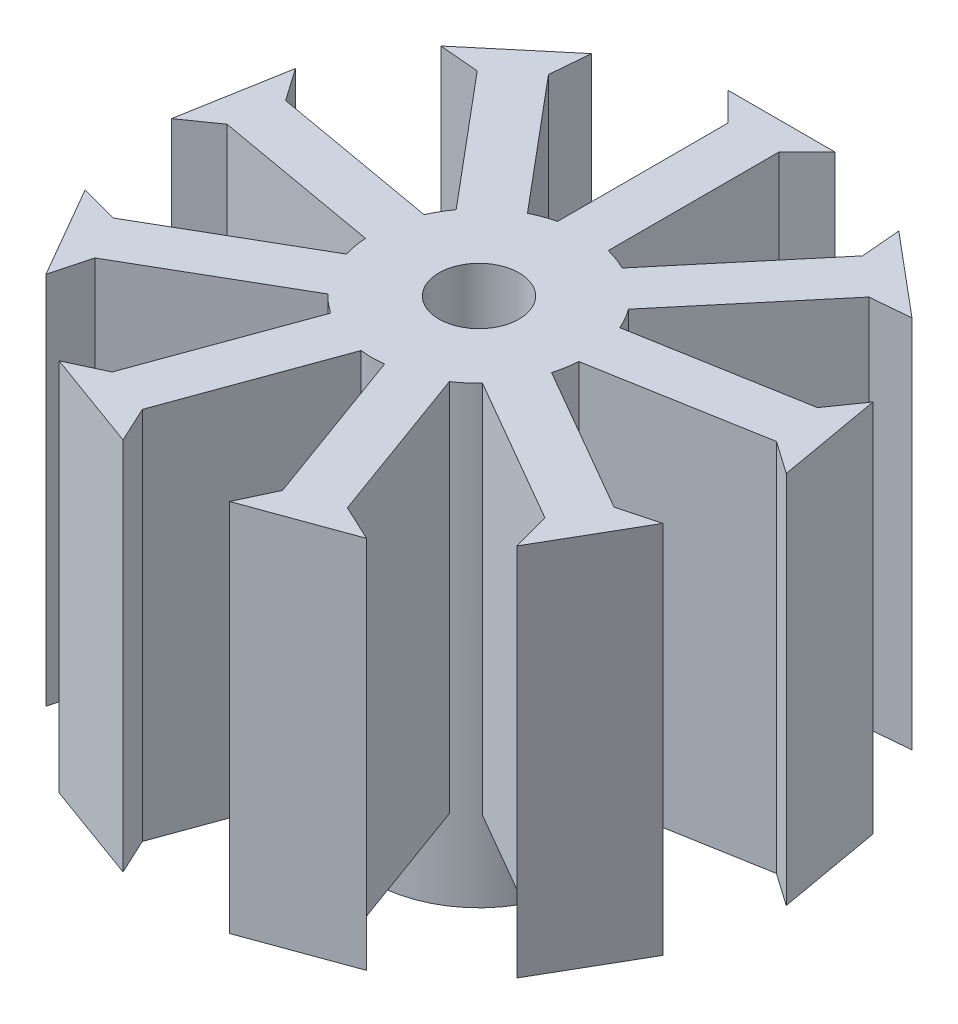
SolidWorks part; units mm, degrees
material "Lega 1060"
ref_plane "Piano frontale" through (0, 0, 0) normal (0, 0, 1) x (1, 0, 0)
ref_plane "Piano superiore" through (0, 0, 0) normal (0, 1, 0) x (1, 0, 0)
ref_plane "Piano destro" through (0, 0, 0) normal (1, 0, 0) x (0, 0, -1)
sketch "Schizzo1" plane through (0, 0, 0) normal (0, 1, 0) x (1, 0, 0)
  circle A0 centre (0, 0) radius 4
extrude "Estrusione-Estrusione1" add sketch "Schizzo1" along normal blind 3
sketch "Schizzo2" plane through (0, 3, 0) normal (0, 1, 0) x (1, 0, 0)
  line L0 (5.8772, 8.4767) -> (1.773, 3.5856)
  line L1 (2, 11.3248) -> (-2, 11.3248)
  line L2 (-0.9465, 10.2713) -> (-0.9465, 3.8864)
  line L3 (2, 11.3248) -> (0.9465, 10.2713)
  line L4 (0.9465, 10.2713) -> (0.9465, 3.8864)
  line L5 (-2, 11.3248) -> (-0.9465, 10.2713)
  line L6 (7.3274, 7.2598) -> (3.2232, 2.3687)
  line L7 (8.8115, 7.3897) -> (7.3274, 7.2598)
  line L8 (8.8115, 7.3897) -> (5.7473, 9.9608)
  line L9 (5.7473, 9.9608) -> (5.8772, 8.4767)
  line L10 (9.9509, 2.7158) -> (3.663, 1.607)
  line L11 (10.2796, 0.8514) -> (3.9917, -0.2573)
  line L12 (11.5, -0.0031) -> (10.2796, 0.8514)
  line L13 (11.5, -0.0031) -> (10.8054, 3.9361)
  line L14 (10.8054, 3.9361) -> (9.9509, 2.7158)
  line L15 (9.3685, -4.3159) -> (3.839, -1.1235)
  line L16 (8.4219, -5.9554) -> (2.8924, -2.7629)
  line L17 (8.8075, -7.3944) -> (8.4219, -5.9554)
  line L18 (8.8075, -7.3944) -> (10.8075, -3.9303)
  line L19 (10.8075, -3.9303) -> (9.3685, -4.3159)
  line L20 (4.4025, -9.3281) -> (2.2187, -3.3283)
  line L21 (2.6235, -9.9756) -> (0.4398, -3.9758)
  line L22 (1.9939, -11.3258) -> (2.6235, -9.9756)
  line L23 (1.9939, -11.3258) -> (5.7527, -9.9577)
  line L24 (5.7527, -9.9577) -> (4.4025, -9.3281)
  line L25 (-2.6235, -9.9756) -> (-0.4398, -3.9758)
  line L26 (-4.4025, -9.3281) -> (-2.2187, -3.3283)
  line L27 (-5.7527, -9.9577) -> (-4.4025, -9.3281)
  line L28 (-5.7527, -9.9577) -> (-1.9939, -11.3258)
  line L29 (-1.9939, -11.3258) -> (-2.6235, -9.9756)
  line L30 (-8.4219, -5.9554) -> (-2.8924, -2.7629)
  line L31 (-9.3685, -4.3159) -> (-3.839, -1.1235)
  line L32 (-10.8075, -3.9303) -> (-9.3685, -4.3159)
  line L33 (-10.8075, -3.9303) -> (-8.8075, -7.3944)
  line L34 (-8.8075, -7.3944) -> (-8.4219, -5.9554)
  line L35 (-10.2796, 0.8514) -> (-3.9917, -0.2573)
  line L36 (-9.9509, 2.7158) -> (-3.663, 1.607)
  line L37 (-10.8054, 3.9361) -> (-9.9509, 2.7158)
  line L38 (-10.8054, 3.9361) -> (-11.5, -0.0031)
  line L39 (-11.5, -0.0031) -> (-10.2796, 0.8514)
  line L40 (-7.3274, 7.2598) -> (-3.2232, 2.3687)
  line L41 (-5.8772, 8.4767) -> (-1.773, 3.5856)
  line L42 (-5.7473, 9.9608) -> (-5.8772, 8.4767)
  line L43 (-5.7473, 9.9608) -> (-8.8115, 7.3897)
  line L44 (-8.8115, 7.3897) -> (-7.3274, 7.2598)
  arc A0 (-3.2232, 2.3687) -> (-3.663, 1.607) centre (0, 0) ccw
  arc A1 (-0.9465, 3.8864) -> (-1.773, 3.5856) centre (0, 0) ccw
  arc A2 (1.773, 3.5856) -> (0.9465, 3.8864) centre (0, 0) ccw
  arc A3 (3.663, 1.607) -> (3.2232, 2.3687) centre (0, 0) ccw
  arc A4 (3.839, -1.1235) -> (3.9917, -0.2573) centre (0, 0) ccw
  arc A5 (2.2187, -3.3283) -> (2.8924, -2.7629) centre (0, 0) ccw
  arc A6 (-0.4398, -3.9758) -> (0.4398, -3.9758) centre (0, 0) ccw
  arc A7 (-2.8924, -2.7629) -> (-2.2187, -3.3283) centre (0, 0) ccw
  arc A8 (-3.9917, -0.2573) -> (-3.839, -1.1235) centre (0, 0) ccw
  point P58 (0, 0)
  dimension "D2" = 4
extrude "Estrusione-Estrusione2" add sketch "Schizzo2" along normal blind 14
sketch "Schizzo3" plane through (0, 17, 0) normal (0, 1, 0) x (1, 0, 0)
  circle A0 centre (0, 0) radius 1.5
extrude "Taglio-Estrusione1" cut sketch "Schizzo3" against normal blind 32
